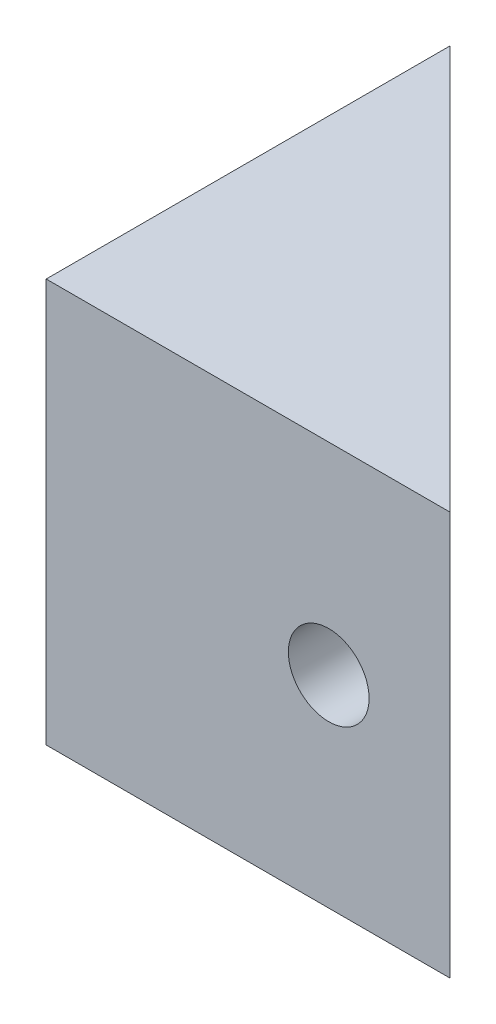
SolidWorks part; units mm, degrees
ref_plane "Front Plane" through (0, 0, 0) normal (0, 0, 1) x (1, 0, 0)
ref_plane "Top Plane" through (0, 0, 0) normal (0, 1, 0) x (1, 0, 0)
ref_plane "Right Plane" through (0, 0, 0) normal (1, 0, 0) x (0, 0, -1)
sketch "Sketch1" plane through (0, 0, 0) normal (0, 1, 0) x (1, 0, 0)
  line L0 (0, 20) -> (0, 0)
  line L1 (0, 0) -> (20, 0)
  line L2 (20, 0) -> (0, 20)
  dimension "D1" = 20
extrude "Boss-Extrude1" add sketch "Sketch1" along normal blind 20
sketch "Sketch2" plane through (0, 0, 0) normal (0, 0, 1) x (1, 0, 0)
  line L0 (20, 10) -> (0, 10) construction
  line L1 (20, 20) -> (20, 0) construction
  line L2 (0, 20) -> (0, 0) construction
  circle A0 centre (14, 10) radius 2
  point P8 (0, 0)
  point P9 (14.2443, 13.6327)
  point P10 (14.6192, 13.8822)
  point P11 (14.7772, 10)
  dimension "D1" = 4
  dimension "D2" = 6
extrude "Cut-Extrude1" cut sketch "Sketch2" against normal through all
ref_plane "Plane1" through (0, 0, 0) normal (0.7071, 0, 0.7071) x (0.7071, 0, -0.7071)
mirror "Mirror1" about plane through (0, 0, 0) normal (0.7071, 0, 0.7071) of "Cut-Extrude1"
